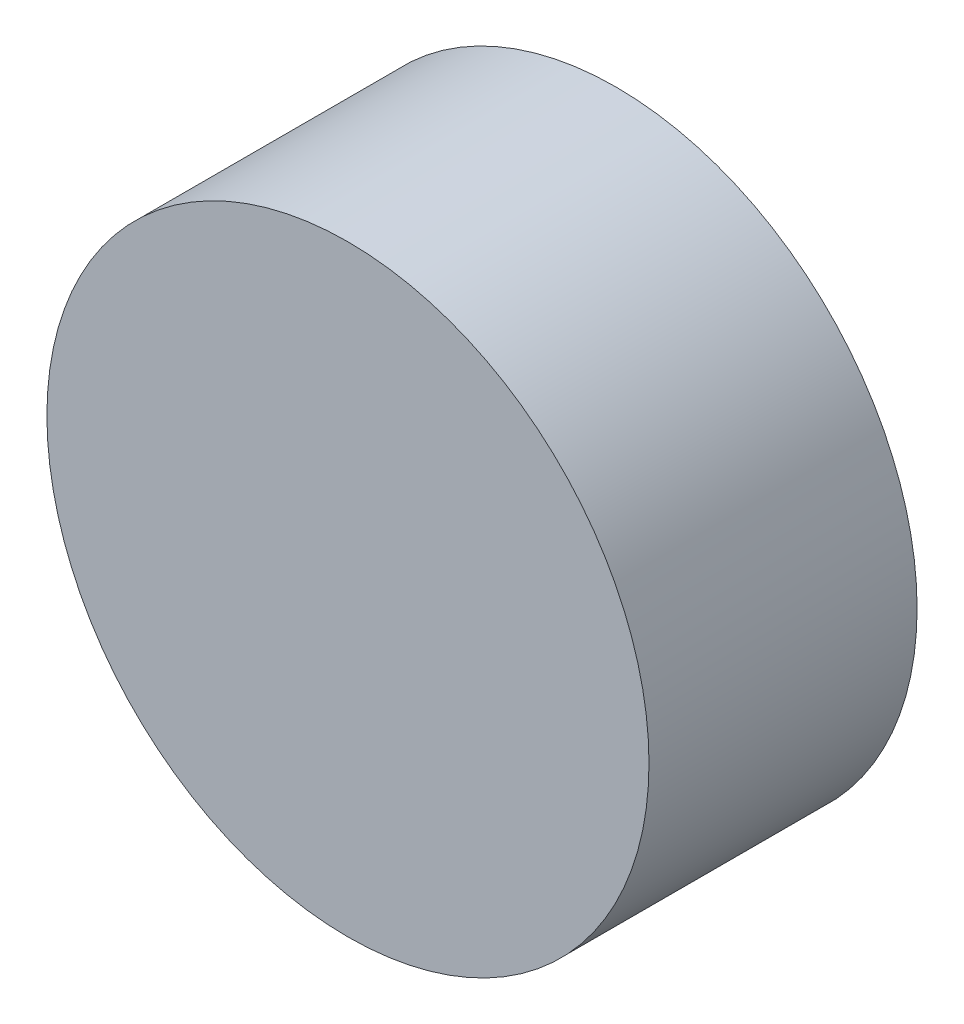
SolidWorks part; units mm, degrees
ref_plane "Front Plane" through (0, 0, 0) normal (0, 0, 1) x (1, 0, 0)
ref_plane "Top Plane" through (0, 0, 0) normal (0, 1, 0) x (1, 0, 0)
ref_plane "Right Plane" through (0, 0, 0) normal (1, 0, 0) x (0, 0, -1)
sketch "CurveSketch" plane through (0, 0, 0) normal (0, 0, 1) x (1, 0, 0)
  circle A0 centre (-11.731, 7.391) radius 13.173
  arc A1 (3.5136, -4.1774) -> (-17.9892, 25.4758) centre (-11.731, 7.391) cw construction
  dimension "D1" = 13.173
extrude "CurveBoss" add sketch "CurveSketch" along normal blind 11.731
